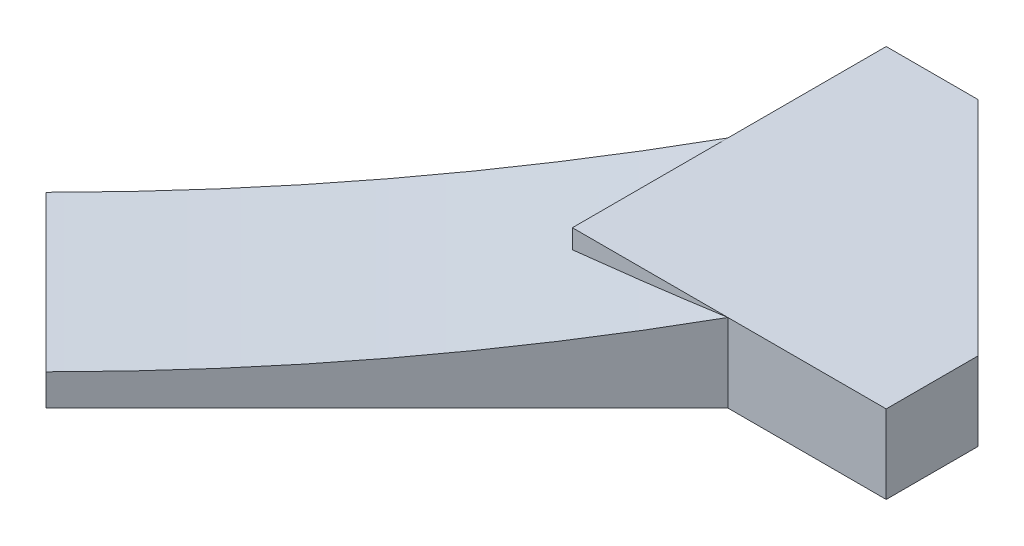
SolidWorks part; units mm, degrees
ref_plane "前视基准面" through (0, 0, 0) normal (0, 0, 1) x (1, 0, 0)
ref_plane "上视基准面" through (0, 0, 0) normal (0, 1, 0) x (1, 0, 0)
ref_plane "右视基准面" through (0, 0, 0) normal (1, 0, 0) x (0, 0, -1)
other "Configuration Table"
sketch "草图1" plane through (0, 0, 0) normal (0, 1, 0) x (1, 0, 0)
  line L2 (0, 20) -> (5.85, 20)
  line L3 (20, 0) -> (20, 5.85)
  line L6 (5.85, 20) -> (20, 5.85)
  line L8 (-21.7272, -11.8198) -> (0, 9.9074)
  line L9 (0, 20) -> (0, 9.9074)
  line L12 (20, 0) -> (14.15, 0)
  line L15 (14.15, 0) -> (9.9074, 0)
  line L16 (9.9074, 0) -> (-11.8198, -21.7272)
  line L17 (-21.7272, -11.8198) -> (-11.8198, -21.7272)
extrude "凸台-拉伸1" add sketch "草图1" along normal blind 5
sketch "草图2" plane through (4.9537, 0, 4.9537) normal (0.7071, 0, 0.7071) x (0.7071, 0, -0.7071)
  line L2 (-23.7213, 5) -> (-23.7213, 0) construction
  line L5 (-23.7213, 2) -> (-23.7213, 5)
  line L6 (-23.7213, 5) -> (7.0056, 5)
  arc A0 (-23.7213, 2) -> (7.0056, 5) centre (-23.7213, 160.8566) ccw
extrude "切除-拉伸1" cut sketch "草图2" against normal blind 20
sketch "草图3" plane through (0, 5, 0) normal (0, 1, 0) x (1, 0, 0)
  line L0 (0, 9.9074) -> (0, 0)
  line L1 (0, 0) -> (9.9074, 0)
  line L2 (9.9074, 0) -> (0, 9.9074)
extrude "凸台-拉伸2" add sketch "草图3" against normal blind 5
